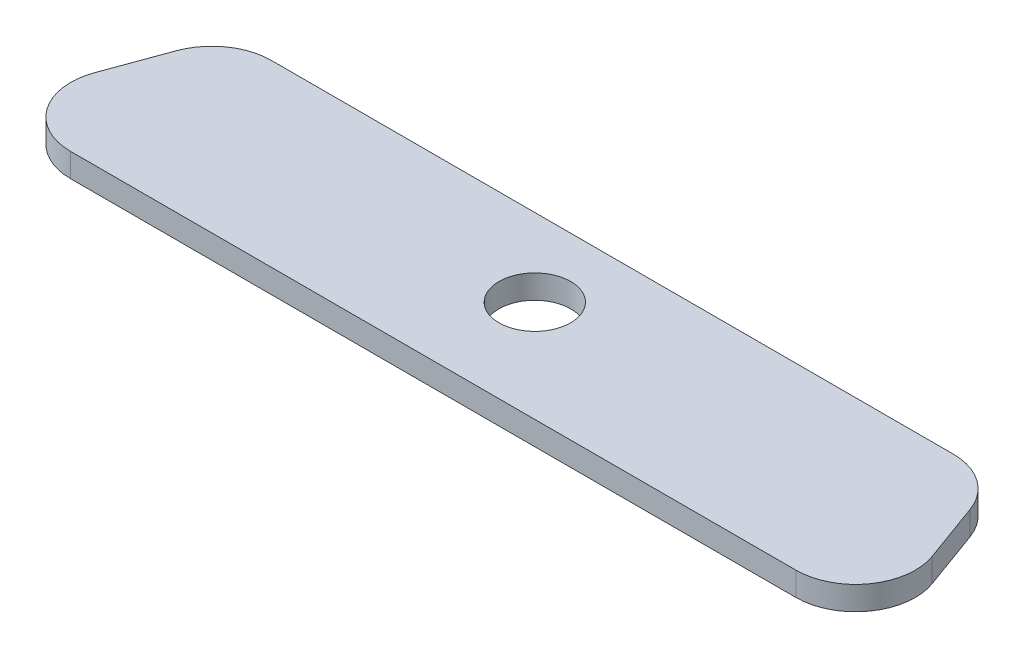
SolidWorks part; units mm, degrees
ref_plane "Front Plane" through (0, 0, 0) normal (0, 0, 1) x (1, 0, 0)
ref_plane "Top Plane" through (0, 0, 0) normal (0, 1, 0) x (1, 0, 0)
ref_plane "Right Plane" through (0, 0, 0) normal (1, 0, 0) x (0, 0, -1)
sketch "Sketch1" plane through (0, 0, 0) normal (0, 1, 0) x (1, 0, 0)
  line L0 (0, 0) -> (30, 0)
  line L5 (30, 0) -> (27.8162, 6)
  line L6 (27.8162, 6) -> (2.1838, 6)
  line L7 (2.1838, 6) -> (0, 0)
  circle A0 centre (15, 3.4) radius 1.2
  point P9 (15, 6)
  dimension "D6" = 2.4
  dimension "D1" = 70
  dimension "D2" = 70
  dimension "D3" = 6
  dimension "D4" = 30
  dimension "D5" = 2.6
extrude "Boss-Extrude1" add sketch "Sketch1" along normal blind 0.7937
fillet "Fillet1" radius 2 4 edges at (2.1838, 0.3969, -6) (0, 0.3969, 0) (27.8162, 0.3969, -6) (30, 0.3969, 0)
